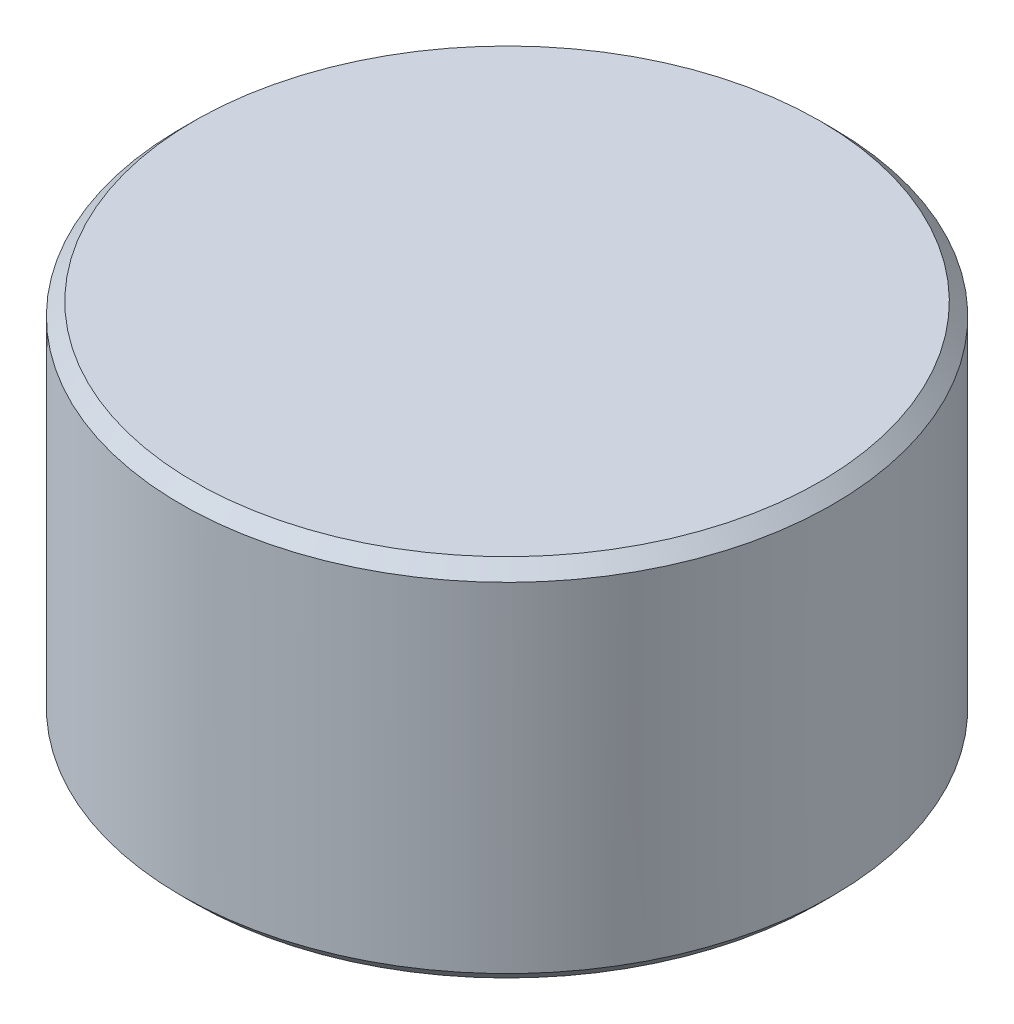
SolidWorks part; units mm, degrees
ref_plane "Front Plane" through (0, 0, 0) normal (0, 0, 1) x (1, 0, 0)
ref_plane "Top Plane" through (0, 0, 0) normal (0, 1, 0) x (1, 0, 0)
ref_plane "Right Plane" through (0, 0, 0) normal (1, 0, 0) x (0, 0, -1)
sketch "Sketch1" plane through (0, 0, 0) normal (0, 1, 0) x (1, 0, 0)
  circle A0 centre (0, 0) radius 2.5
  dimension "D1" = 5
extrude "Boss-Extrude1" add sketch "Sketch1" along normal blind 2.8
chamfer "Chamfer1" distance 0.1 angle 45 2 edges at (0, 0, 2.5) (0, 2.8, 2.5)
